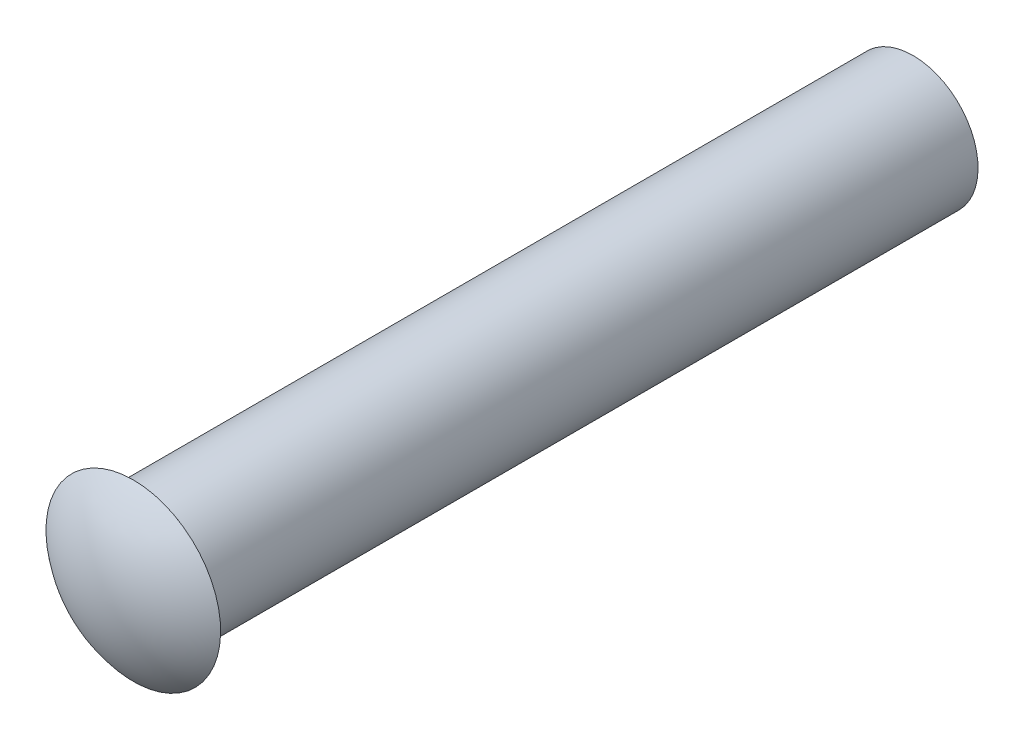
SolidWorks part; units mm, degrees
ref_plane "Front Plane" through (0, 0, 0) normal (0, 0, 1) x (1, 0, 0)
ref_plane "Top Plane" through (0, 0, 0) normal (0, 1, 0) x (1, 0, 0)
ref_plane "Right Plane" through (0, 0, 0) normal (1, 0, 0) x (0, 0, -1)
sketch "Sketch1" plane through (0, 0, 0) normal (1, 0, 0) x (0, 0, -1)
  line L0 (19.8374, 0) -> (0, 0)
  line L2 (0.7874, 2.1336) -> (0.7874, 1.5875)
  line L3 (0.7874, 1.5875) -> (19.8374, 1.5875)
  line L4 (19.8374, 1.5875) -> (19.8374, 0)
  arc A1 (0, 0) -> (0.7874, 2.1336) centre (3.2844, 0) cw
  dimension "D1" = 1.5875
  dimension "D2" = 19.05
  dimension "D3" = 0.7874
  dimension "D4" = 2.1336
revolve "Revolve1" add sketch "Sketch1" angle 360 about L0
